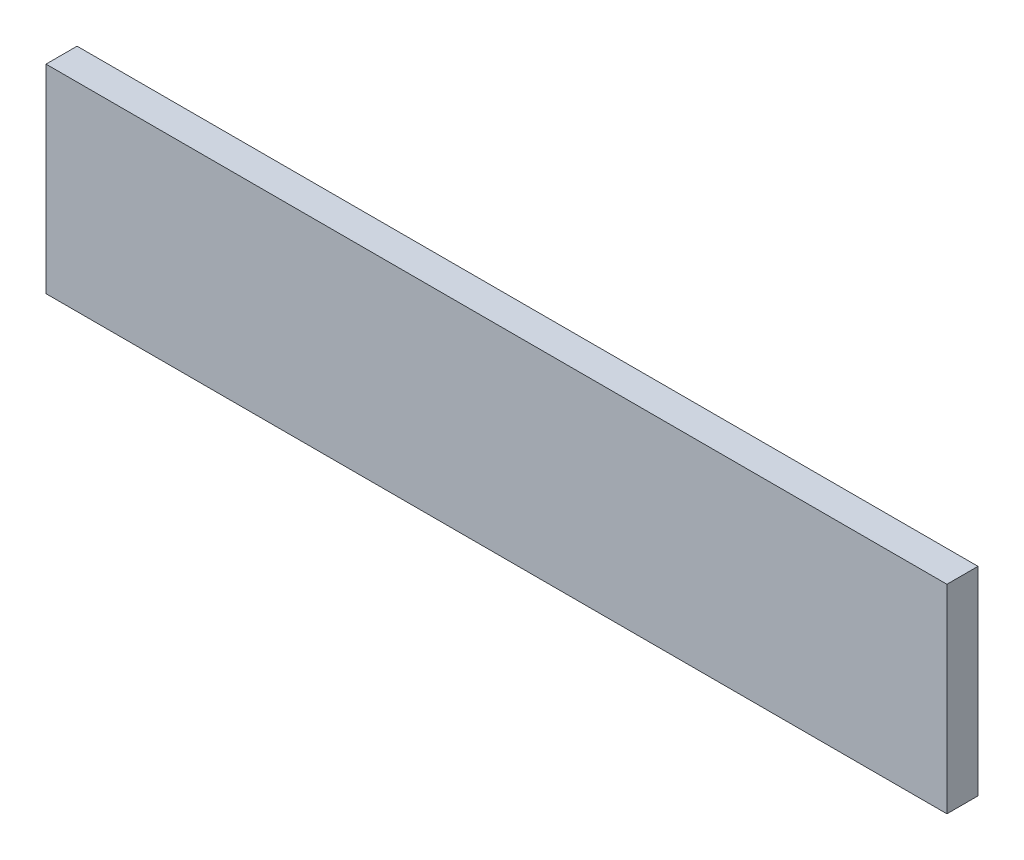
SolidWorks part; units mm, degrees
ref_plane "Front Plane" through (0, 0, 0) normal (0, 0, 1) x (1, 0, 0)
ref_plane "Top Plane" through (0, 0, 0) normal (0, 1, 0) x (1, 0, 0)
ref_plane "Right Plane" through (0, 0, 0) normal (1, 0, 0) x (0, 0, -1)
sketch "Sketch2" plane through (0, 0, -254.6639) normal (0, 0, -1) x (-1, 0, 0)
  line L0 (-189.8115, 8.6051) -> (225.6758, 8.6051) construction
  line L1 (-111.2956, -23.3949) -> (178.7044, -23.3949)
  line L2 (-111.2956, -23.3949) -> (-111.2956, 40.6051)
  line L3 (-111.2956, 40.6051) -> (178.7044, 40.6051)
  line L4 (178.7044, -23.3949) -> (178.7044, 40.6051)
  line L5 (-111.2956, -23.3949) -> (178.7044, 40.6051) construction
  line L6 (-111.2956, 40.6051) -> (178.7044, -23.3949) construction
  line L7 (33.7044, -64.1446) -> (33.7044, 124.7881) construction
  line L8 (-86.2956, 43.6051) -> (-26.2956, 43.6051) construction
  line L9 (-91.2956, -21.3949) -> (-91.2956, 38.6051) construction
  point P0 (33.7044, 8.6051)
  dimension "D1" = 3
  dimension "D2" = 20
extrude "Boss-Extrude1" add sketch "Sketch2" along normal blind 10
